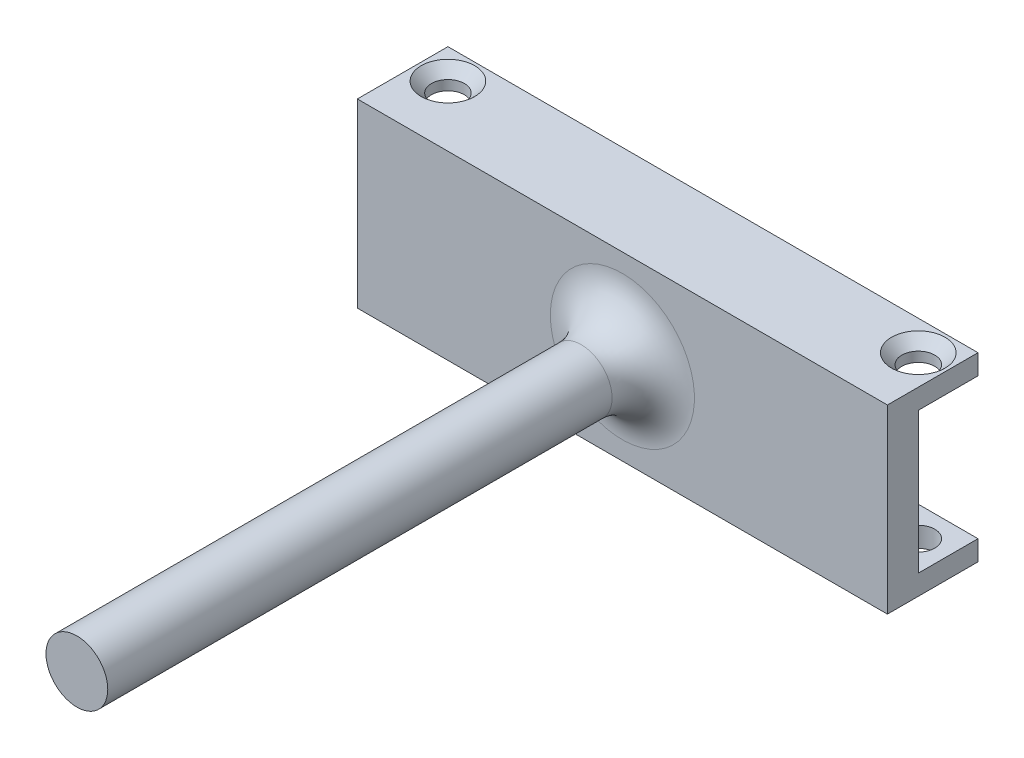
SolidWorks part; units mm, degrees
ref_plane "Front Plane" through (0, 0, 0) normal (0, 0, 1) x (1, 0, 0)
ref_plane "Top Plane" through (0, 0, 0) normal (0, 1, 0) x (1, 0, 0)
ref_plane "Right Plane" through (0, 0, 0) normal (1, 0, 0) x (0, 0, -1)
sketch "Sketch1" plane through (0, 0, 0) normal (0, 0, 1) x (1, 0, 0)
  line L1 (0, 0) -> (51.5, 0)
  line L2 (0, 0) -> (0, 17.6)
  line L3 (0, 17.6) -> (51.5, 17.6)
  line L4 (51.5, 0) -> (51.5, 17.6)
  dimension "D1" = 51.5
  dimension "D2" = 17.6
extrude "Boss-Extrude1" add sketch "Sketch1" along normal blind 8.8
sketch "Sketch2" plane through (0, 0, 0) normal (0, 0, -1) x (-1, 0, 0)
  line L0 (-51.5, 0) -> (-51.5, 17.6) construction
  line L1 (-51.5, 1.95) -> (0, 1.95)
  line L2 (-51.5, 1.95) -> (-51.5, 15.65)
  line L3 (-51.5, 15.65) -> (0, 15.65)
  line L4 (0, 1.95) -> (0, 15.65)
  line L5 (0, 17.6) -> (0, 0) construction
  line L6 (0, 0) -> (-51.5, 0) construction
  dimension "D1" = 13.7
  dimension "D2" = 1.95
extrude "Cut-Extrude1" cut sketch "Sketch2" against normal blind 5.8
sketch "Sketch3" plane through (0, 17.6, 0) normal (0, 1, 0) x (1, 0, 0)
  line L0 (0, -8.8) -> (0, 0) construction
  line L2 (51.5, 0) -> (0, 0) construction
  line L3 (51.5, -8.8) -> (51.5, 0) construction
  circle A0 centre (2.9, -2.9) radius 1.6
  circle A1 centre (48.6, -2.9) radius 1.6
  dimension "D1" = 3.2
  dimension "D4" = 3.2
  dimension "D2" = 2.9
  dimension "D3" = 2.9
  dimension "D5" = 2.9
  dimension "D6" = 2.9
extrude "Cut-Extrude2" cut sketch "Sketch3" against normal blind 17.8
chamfer "Chamfer1" distance 1 angle 45 2 edges at (48.6, 17.6, 4.5) (2.9, 17.6, 4.5)
sketch "Sketch4" plane through (0, 0, 8.8) normal (0, 0, 1) x (1, 0, 0)
  line L0 (51.5, 17.6) -> (0, 17.6) construction
  line L1 (51.5, 0) -> (51.5, 17.6) construction
  circle A0 centre (25.75, 8.8) radius 3
  dimension "D3" = 6
  dimension "D1" = 8.8
  dimension "D2" = 25.75
extrude "Boss-Extrude2" add sketch "Sketch4" along normal blind 53
fillet "Fillet1" radius 4 1 edges at (22.75, 8.8, 8.8)
